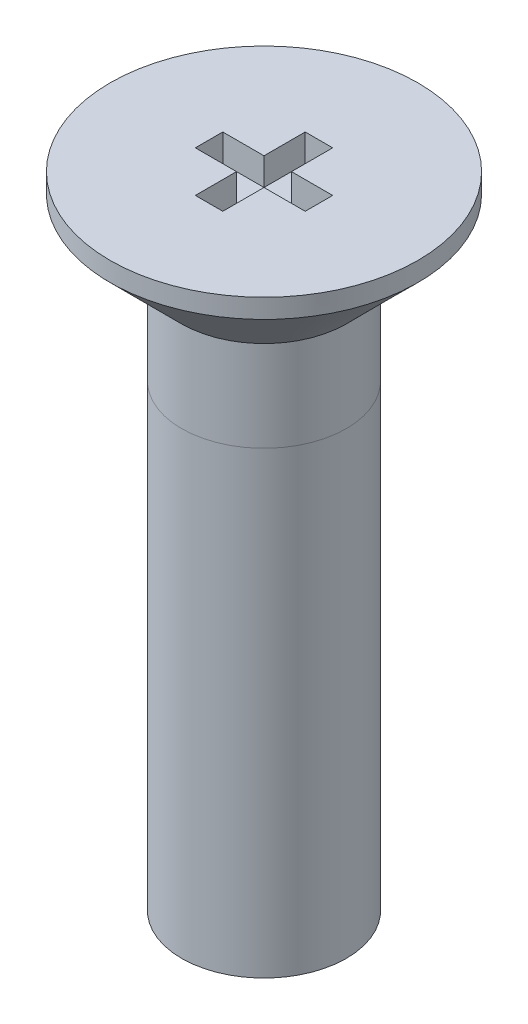
SolidWorks part; units mm, degrees
ref_plane "Front Plane" through (0, 0, 0) normal (0, 0, 1) x (1, 0, 0)
ref_plane "Top Plane" through (0, 0, 0) normal (0, 1, 0) x (1, 0, 0)
ref_plane "Right Plane" through (0, 0, 0) normal (1, 0, 0) x (0, 0, -1)
sketch "Sketch1" plane through (0, 0, 0) normal (0, 1, 0) x (1, 0, 0)
  circle A0 centre (0, 0) radius 1.5
  dimension "D1" = 3
extrude "Boss-Extrude1" add sketch "Sketch1" along normal blind 8.35
sketch "Sketch2" plane through (0, 8.35, 0) normal (0, 1, 0) x (1, 0, 0)
  circle A0 centre (0, 0) radius 1.5
  circle A1 centre (0, 0) radius 1.5 construction
extrude "Boss-Extrude2" add sketch "Sketch2" along normal blind 1.65 separate body
sketch "Sketch3" plane through (0, 10, 0) normal (0, 1, 0) x (1, 0, 0)
  circle A0 centre (0, 0) radius 2.8
  dimension "D1" = 5.6
extrude "Boss-Extrude3" add sketch "Sketch3" along normal blind 1.65
sketch "Sketch6" plane through (0, 0, 0) normal (0, 0, 1) x (1, 0, 0)
  line L0 (1.5, 10) -> (2.8, 11.3)
  line L2 (0, 0) -> (0, 11.65) construction
  line L3 (2.8, 11.65) -> (-2.8, 11.65) construction
  line L4 (2.8, 10) -> (2.8, 11.65) construction
  line L5 (-2.8, 10) -> (2.8, 10) construction
  line L6 (1.5, 10) -> (2.8, 10)
  line L7 (2.8, 10) -> (2.8, 11.3)
  dimension "D1" = 45
revolve "Cut-Revolve1" cut sketch "Sketch6" angle 360 about L2
sketch "Sketch7" plane through (0, 11.65, 0) normal (0, 1, 0) x (1, 0, 0)
  line L0 (0, 1) -> (0, -1) construction
  line L1 (-1, 0) -> (1, 0) construction
  line L3 (-0.25, 1) -> (0.25, 1)
  line L4 (-0.25, 1) -> (-0.25, -1)
  line L5 (-0.25, -1) -> (0.25, -1)
  line L6 (0.25, 1) -> (0.25, -1)
  line L7 (-1, 0.25) -> (1, 0.25)
  line L8 (-1, 0.25) -> (-1, -0.25)
  line L9 (-1, -0.25) -> (1, -0.25)
  line L10 (1, 0.25) -> (1, -0.25)
  circle A0 centre (0, 0) radius 2.8 construction
  dimension "D1" = 1
  dimension "D2" = 0.5
extrude "Cut-Extrude2" cut sketch "Sketch7" against normal blind 0.5 contours L4 L7 L6 L3 | L4 L9 L6 L7 | L10 L7 L6 L9 | L9 L4 L5 L6 | L8 L9 L4 L7
